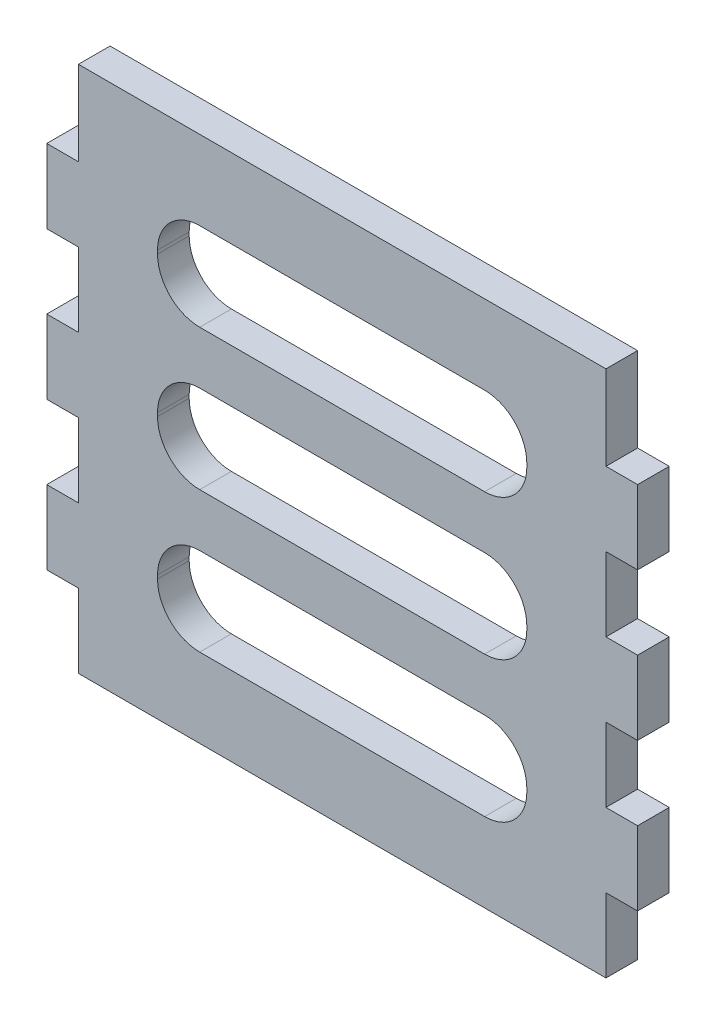
SolidWorks part; units mm, degrees
ref_plane "Front Plane" through (0, 0, 0) normal (0, 0, 1) x (1, 0, 0)
ref_plane "Top Plane" through (0, 0, 0) normal (0, 1, 0) x (1, 0, 0)
ref_plane "Right Plane" through (0, 0, 0) normal (1, 0, 0) x (0, 0, -1)
sketch "Sketch1" plane through (0, 0, 0) normal (0, 0, 1) x (1, 0, 0)
  line L0 (0, 0) -> (0, 7)
  line L1 (0, 0) -> (-50, 0)
  line L2 (0, 0) -> (0, 50) construction
  line L3 (0, 50) -> (-50, 50)
  line L4 (-50, 0) -> (-50, 50) construction
  line L5 (0, 7) -> (3, 7)
  line L6 (3, 7) -> (3, 14)
  line L7 (3, 14) -> (0, 14)
  line L8 (0, 14) -> (0, 21)
  line L9 (0, 21) -> (3, 21)
  line L10 (3, 21) -> (3, 28)
  line L11 (3, 28) -> (0, 28)
  line L12 (0, 28) -> (0, 35)
  line L13 (0, 35) -> (3, 35)
  line L14 (3, 35) -> (3, 42)
  line L15 (3, 42) -> (0, 42)
  line L16 (0, 42) -> (0, 50)
  line L17 (-25, 50) -> (-25, 0) construction
  line L18 (-50, 42) -> (-50, 50)
  line L19 (-53, 42) -> (-50, 42)
  line L20 (-53, 35) -> (-53, 42)
  line L21 (-50, 35) -> (-53, 35)
  line L22 (-50, 28) -> (-50, 35)
  line L23 (-53, 28) -> (-50, 28)
  line L24 (-53, 21) -> (-53, 28)
  line L25 (-50, 21) -> (-53, 21)
  line L26 (-50, 14) -> (-50, 21)
  line L27 (-53, 14) -> (-50, 14)
  line L28 (-53, 7) -> (-53, 14)
  line L29 (-50, 7) -> (-53, 7)
  line L30 (-50, 0) -> (-50, 7)
  line L32 (-38.5, 42.5) -> (-11.5, 42.5)
  line L33 (-42.5, 38.5) -> (-42.5, 38.1667)
  line L34 (-38.5, 34.1667) -> (-11.5, 34.1667)
  line L35 (-7.5, 38.5) -> (-7.5, 38.1667)
  line L36 (-38.5, 29.1667) -> (-11.5, 29.1667)
  line L37 (-42.5, 25.1667) -> (-42.5, 24.8333)
  line L38 (-38.5, 20.8333) -> (-11.5, 20.8333)
  line L39 (-7.5, 25.1667) -> (-7.5, 24.8333)
  line L40 (-11.5, 15.8333) -> (-38.5, 15.8333)
  line L41 (-7.5, 11.8333) -> (-7.5, 11.5)
  line L42 (-11.5, 7.5) -> (-38.5, 7.5)
  line L43 (-42.5, 11.8333) -> (-42.5, 11.5)
  arc A0 (-38.5, 15.8333) -> (-42.5, 11.8333) centre (-38.5, 11.8333) ccw
  arc A1 (-7.5, 11.5) -> (-11.5, 7.5) centre (-11.5, 11.5) cw
  arc A2 (-38.5, 7.5) -> (-42.5, 11.5) centre (-38.5, 11.5) cw
  arc A3 (-11.5, 15.8333) -> (-7.5, 11.8333) centre (-11.5, 11.8333) cw
  arc A4 (-11.5, 29.1667) -> (-7.5, 25.1667) centre (-11.5, 25.1667) cw
  arc A5 (-42.5, 24.8333) -> (-38.5, 20.8333) centre (-38.5, 24.8333) ccw
  arc A6 (-11.5, 20.8333) -> (-7.5, 24.8333) centre (-11.5, 24.8333) ccw
  arc A7 (-38.5, 29.1667) -> (-42.5, 25.1667) centre (-38.5, 25.1667) ccw
  arc A8 (-11.5, 42.5) -> (-7.5, 38.5) centre (-11.5, 38.5) cw
  arc A9 (-42.5, 38.1667) -> (-38.5, 34.1667) centre (-38.5, 38.1667) ccw
  arc A10 (-11.5, 34.1667) -> (-7.5, 38.1667) centre (-11.5, 38.1667) ccw
  arc A11 (-38.5, 42.5) -> (-42.5, 38.5) centre (-38.5, 38.5) ccw
  dimension "D11" = 4
  dimension "D1" = 50
  dimension "D2" = 50
  dimension "D3" = 7
  dimension "D4" = 3
  dimension "D5" = 7.5
  dimension "D6" = 5
  dimension "D7" = 5
  dimension "D8" = 7.5
  dimension "D9" = 7.5
  dimension "D10" = 7.5
extrude "Boss-Extrude1" add sketch "Sketch1" along normal blind 3
